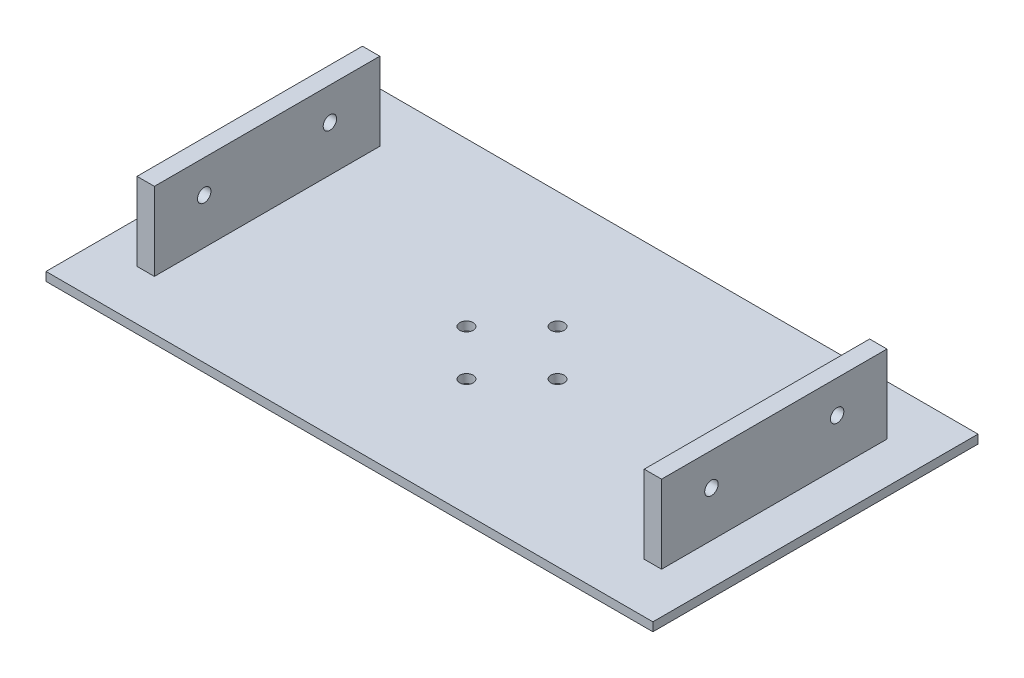
SolidWorks part; units mm, degrees
ref_plane "前视基准面" through (0, 0, 0) normal (0, 0, 1) x (1, 0, 0)
ref_plane "上视基准面" through (0, 0, 0) normal (0, 1, 0) x (1, 0, 0)
ref_plane "右视基准面" through (0, 0, 0) normal (1, 0, 0) x (0, 0, -1)
other "Configuration Table"
sketch "草图1" plane through (0, 0, 0) normal (0, 1, 0) x (1, 0, 0)
  line L0 (-70, 37.5) -> (70, -37.5) construction
  line L1 (-70, 37.5) -> (70, 37.5)
  line L2 (-70, 37.5) -> (-70, -37.5)
  line L3 (-70, -37.5) -> (70, -37.5)
  line L4 (70, 37.5) -> (70, -37.5)
  line L5 (70, 37.5) -> (-70, -37.5) construction
  line L6 (-60.5, 26) -> (-60.5, -26)
  line L7 (-77, 0) -> (77, 0) construction
  line L8 (-60.5, 26) -> (-56.5, 26)
  line L9 (-56.5, 26) -> (-56.5, -26)
  line L10 (-56.5, -26) -> (-60.5, -26)
  line L11 (0, -41.25) -> (0, 41.25) construction
  line L12 (56.5, 26) -> (56.5, -26)
  line L13 (60.5, 26) -> (56.5, 26)
  line L14 (60.5, 26) -> (60.5, -26)
  line L15 (56.5, -26) -> (60.5, -26)
  point P4 (0, 0)
  point P5 (-60.5, 26)
  point P9 (-60.5, 0)
  dimension "D1" = 75
  dimension "D2" = 140
  dimension "D3" = 60.5
  dimension "D4" = 52
  dimension "D5" = 56.5
extrude "凸台-拉伸1" add sketch "草图1" along normal blind 2 contours L2 L1 L4 L3
sketch "草图2" plane through (0, 2, 0) normal (0, 1, 0) x (1, 0, 0)
  line L0 (56.5, -26) -> (60.5, -26) construction
  line L1 (60.5, 26) -> (60.5, -26) construction
  line L2 (56.5, 26) -> (56.5, -26) construction
  line L3 (60.5, 26) -> (56.5, 26) construction
  line L4 (-56.5, -26) -> (-60.5, -26) construction
  line L5 (-60.5, 26) -> (-60.5, -26) construction
  line L6 (-60.5, 26) -> (-56.5, 26) construction
  line L7 (-56.5, 26) -> (-56.5, -26) construction
  line L8 (56.5, -26) -> (60.5, -26)
  line L9 (60.5, 26) -> (60.5, -26)
  line L10 (56.5, 26) -> (56.5, -26)
  line L11 (60.5, 26) -> (56.5, 26)
  line L12 (-56.5, -26) -> (-60.5, -26)
  line L13 (-60.5, 26) -> (-60.5, -26)
  line L14 (-60.5, 26) -> (-56.5, 26)
  line L15 (-56.5, 26) -> (-56.5, -26)
  point P0 (-60.5, 26)
extrude "凸台-拉伸2" add sketch "草图2" along normal blind 18
sketch "草图3" plane through (-60.5, 0, 0) normal (-1, 0, 0) x (0, 0, 1)
  line L0 (0, -11) -> (0, 11) construction
  line L1 (-26, 20) -> (26, 20) construction
  line L3 (0, 20) -> (0, -18.3443) construction
  circle A0 centre (-14.5, 12.5) radius 1.55
  circle A1 centre (14.5, 12.5) radius 1.55
  point P0 (-14.5, 12.5)
  dimension "D2" = 7.5
  dimension "D1" = 14.5
extrude "切除-拉伸1" cut sketch "草图3" against normal blind 15
mirror "镜向1" about plane through (0, 0, 0) normal (1, 0, 0) of "切除-拉伸1"
sketch "草图5" plane through (0, 0, 0) normal (0, -1, 0) x (-1, 0, 0)
  line L0 (-70, 37.5) -> (70, -37.5) construction
  circle A0 centre (0, 0) radius 10.5 construction
  circle A1 centre (0, -10.5) radius 1.55
  circle A2 centre (-10.5, 0) radius 1.55
  circle A3 centre (10.5, 0) radius 1.55
  circle A4 centre (0, 10.5) radius 1.55
extrude "切除-拉伸2" cut sketch "草图5" against normal blind 15
